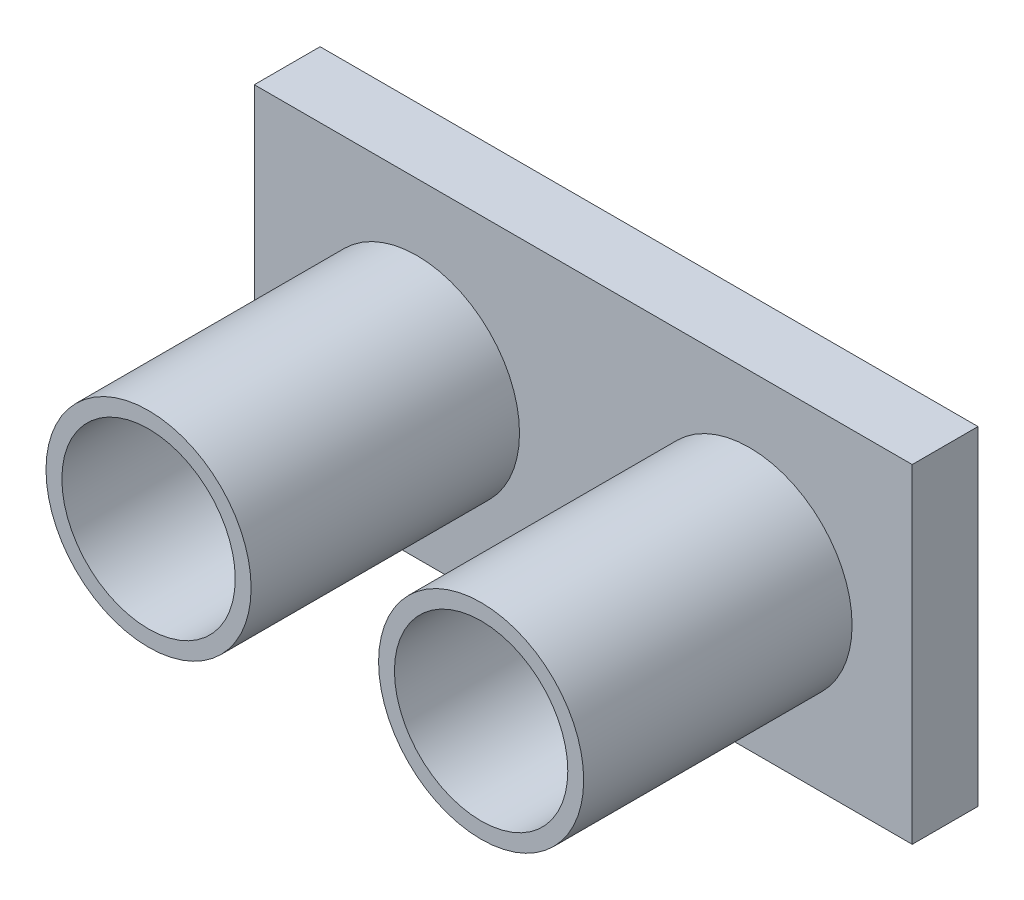
SolidWorks part; units mm, degrees
ref_plane "Front Plane" through (0, 0, 0) normal (0, 0, 1) x (1, 0, 0)
ref_plane "Top Plane" through (0, 0, 0) normal (0, 1, 0) x (1, 0, 0)
ref_plane "Right Plane" through (0, 0, 0) normal (1, 0, 0) x (0, 0, -1)
sketch "Sketch1" plane through (0, 0, 0) normal (0, 0, 1) x (1, 0, 0)
  line L1 (0, 0) -> (-100, 0)
  line L2 (0, 0) -> (0, 50)
  line L3 (0, 50) -> (-100, 50)
  line L4 (-100, 0) -> (-100, 50)
  dimension "D1" = 100
  dimension "D2" = 50
extrude "Boss-Extrude1" add sketch "Sketch1" along normal blind 10
sketch "Sketch2" plane through (0, 0, 0) normal (0, 0, 1) x (1, 0, 0)
  line L0 (-50, 63.5604) -> (-50, -12.704) construction
  circle A0 centre (-75.2752, 24.288) radius 15.5879
  circle A1 centre (-75.2752, 24.288) radius 13.1752
  circle A2 centre (-24.7248, 24.288) radius 13.1752
  circle A3 centre (-24.7248, 24.288) radius 15.5879
extrude "Boss-Extrude2" add sketch "Sketch2" along normal blind 50.8
